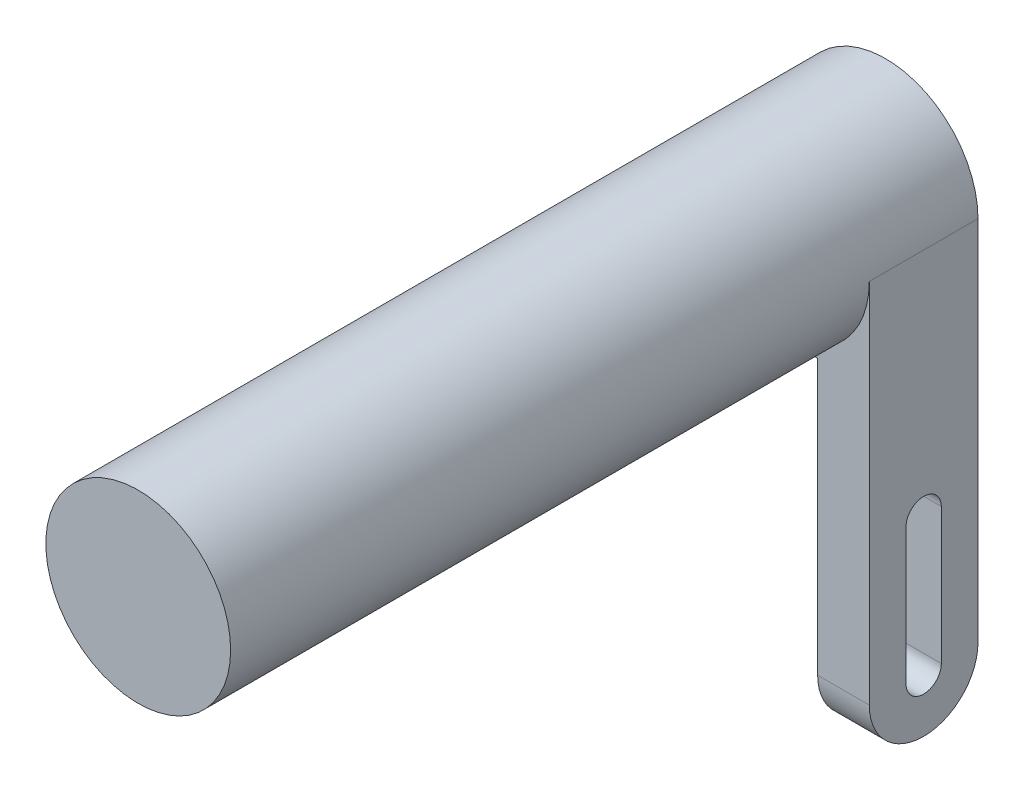
SolidWorks part; units mm, degrees
ref_plane "Plan de face" through (0, 0, 0) normal (0, 0, 1) x (1, 0, 0)
ref_plane "Plan de dessus" through (0, 0, 0) normal (0, 1, 0) x (1, 0, 0)
ref_plane "Plan de droite" through (0, 0, 0) normal (1, 0, 0) x (0, 0, -1)
sketch "Esquisse5" plane through (0, 0, 0) normal (0, 0, 1) x (1, 0, 0)
  circle A0 centre (0, 0) radius 3.4
  circle A1 centre (0, 0) radius 2.6
  dimension "D1" = 5.2
  dimension "D2" = 0.8
extrude "Boss.-Extru.1" add sketch "Esquisse5" along normal blind 27
sketch "Esquisse6" plane through (0, 0, 27) normal (0, 0, 1) x (1, 0, 0)
  circle A1 centre (0, 0) radius 3.4
  circle A2 centre (0, 0) radius 3.4
  dimension "D1" = 0
extrude "Boss.-Extru.2" add sketch "Esquisse6" along normal blind 0.5
sketch3d "Esquisse3D2" plane through (0, 0, 0) normal (0, 0, 1) x (1, 0, 0)
sketch "Esquisse8" plane through (0, 0, 0) normal (-1, 0, 0) x (0, 0, 1)
  line L1 (27.5, 3.4) -> (0, 3.4) construction
  point P0 (-1, 0)
  dimension "D1" = 3.4
sketch "Esquisse9" plane through (0, 0, 0) normal (1, 0, 0) x (0, 0, -1)
  line L0 (-2, -3.4) -> (-2, -13.5) construction
  line L1 (-27.5, -3.4) -> (0, -3.4) construction
  line L2 (0, -3.4) -> (0, -13.5)
  line L3 (-4, -3.4) -> (-4, -13.5)
  line L4 (-2, -13.5) -> (-2, -8.5) construction
  line L5 (-2.65, -13.5) -> (-2.65, -8.5)
  line L6 (-1.35, -13.5) -> (-1.35, -8.5)
  line L7 (-4, -3.4) -> (0, -3.4)
  arc A0 (0, -3.4) -> (-4, -3.4) centre (-2, -3.4) ccw construction
  arc A1 (-4, -13.5) -> (0, -13.5) centre (-2, -13.5) ccw
  arc A2 (-2.65, -13.5) -> (-1.35, -13.5) centre (-2, -13.5) ccw
  arc A3 (-1.35, -8.5) -> (-2.65, -8.5) centre (-2, -8.5) ccw
  point P4 (-2, -8.45)
  point P11 (-2, -11)
  dimension "D1" = 13.5
  dimension "D2" = 5
extrude "Boss.-Extru.4" add sketch "Esquisse9" along normal up to surface (1.9 mm away) from offset 1.5 separate body contours L3 A1 L2 L7 A3 L6 A2 L5
sketch "Esquisse10" plane through (0, 0, 0) normal (0, 0, -1) x (-1, 0, 0)
  line L0 (-3.4, -3.4) -> (-1.5, -3.4) construction
  line L1 (-3.4, -3.4) -> (0, -3.4)
  line L2 (-3.4, -3.4) -> (-3.4, 0)
  circle A2 centre (0, 0) radius 3.4 construction
  arc A4 (-3.4, 0) -> (0, -3.4) centre (0, 0) ccw
extrude "Boss.-Extru.5" add sketch "Esquisse10" against normal up to surface (4 mm away) up to face at (2.45, -8.45, 4)
